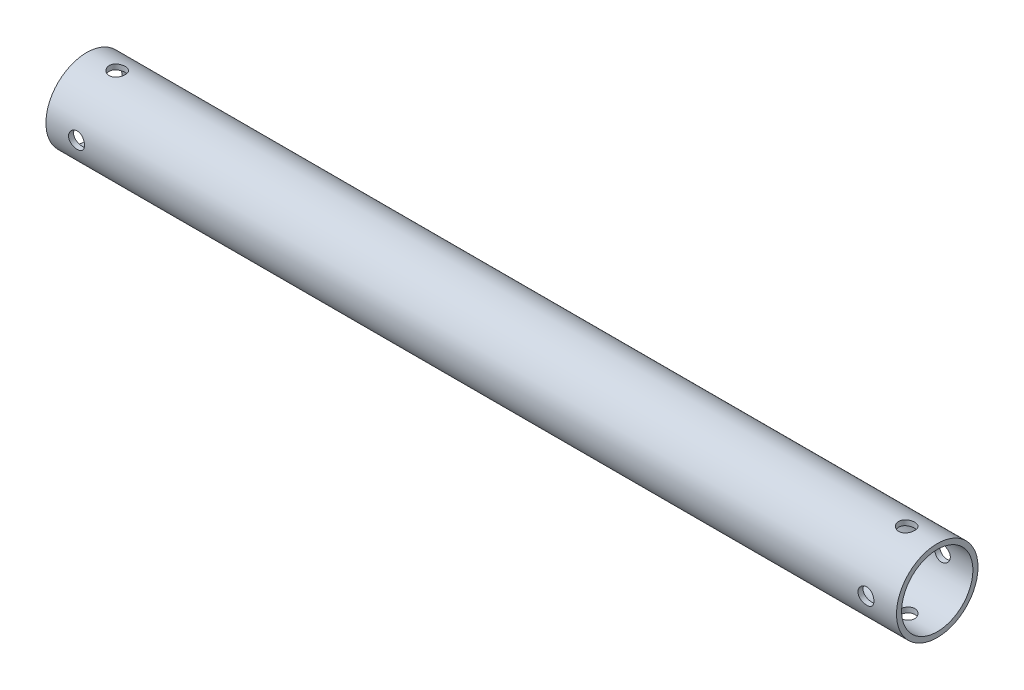
SolidWorks part; units mm, degrees
material "PC High Viscosity"
ref_plane "Front Plane" through (0, 0, 0) normal (0, 0, 1) x (1, 0, 0)
ref_plane "Top Plane" through (0, 0, 0) normal (0, 1, 0) x (1, 0, 0)
ref_plane "Right Plane" through (0, 0, 0) normal (1, 0, 0) x (0, 0, -1)
sketch "Sketch1" plane through (0, 0, 0) normal (1, 0, 0) x (0, 0, -1)
  circle A0 centre (0, 0) radius 12.7
  dimension "D1" = 25.4
extrude "Extrude-Thin1" add sketch "Sketch1" along normal mid plane 265.1125 thin thin type one direction reverse wall 1.5875
sketch "Sketch2" plane through (0, 0, 0) normal (0, 0, 1) x (1, 0, 0)
  line L0 (-132.5562, -12.7) -> (132.5562, -12.7) construction
  line L1 (70.2813, -12.7) -> (91.2812, -12.7)
  line L2 (70.2813, -12.7) -> (70.2813, 12.7)
  line L3 (70.2813, 12.7) -> (91.2812, 12.7)
  line L4 (91.2812, -12.7) -> (91.2812, 12.7)
  line L5 (132.5562, 12.7) -> (-132.5562, 12.7) construction
  line L6 (132.5562, -12.7) -> (132.5562, 12.7) construction
  line L7 (0, 0) -> (0, 11.1276) construction
  line L8 (-91.2812, -12.7) -> (-91.2812, 12.7)
  line L9 (-70.2813, 12.7) -> (-91.2812, 12.7)
  line L10 (-70.2813, -12.7) -> (-70.2813, 12.7)
  line L11 (-70.2813, -12.7) -> (-91.2812, -12.7)
  line L13 (132.5562, -12.7) -> (130.2321, -12.7)
  line L14 (132.5562, -12.7) -> (132.5562, 12.7)
  line L15 (132.5562, 12.7) -> (130.2321, 12.7)
  line L16 (130.2321, -12.7) -> (130.2321, 12.7)
  dimension "D1" = 41.275
  dimension "D2" = 21
  dimension "D3" = 2.3241
sketch "Sketch3" plane through (0, 0, 0) normal (0, 0, 1) x (1, 0, 0)
  line L0 (132.5562, -11.1125) -> (132.5562, 11.1125) construction
  line L1 (-132.5562, 12.7) -> (-132.5562, -12.7) construction
  circle A0 centre (123.0312, 0) radius 2.4892
  circle A1 centre (-123.0312, 0) radius 2.4892
  dimension "D1" = 4.9784
  dimension "D2" = 9.525
  dimension "D3" = 9.525
extrude "Cut-Extrude1" cut sketch "Sketch3" against normal through all both and the other way through all
sketch "Sketch4" plane through (0, 0, 0) normal (0, 1, 0) x (1, 0, 0)
  line L0 (132.5562, -11.1125) -> (132.5562, 11.1125) construction
  line L1 (0, 12.7) -> (0, -12.7) construction
  line L2 (-120.5421, -12.7) -> (120.542, -12.7) construction
  line L3 (120.542, 12.7) -> (-120.5421, 12.7) construction
  circle A0 centre (123.0312, 0) radius 2.4892
  circle A1 centre (-123.0312, 0) radius 2.4892
  dimension "D1" = 4.9784
  dimension "D2" = 9.525
extrude "Cut-Extrude2" cut sketch "Sketch4" against normal through all both and the other way through all
equation "\"D2@Sketch2\"=21mm"
